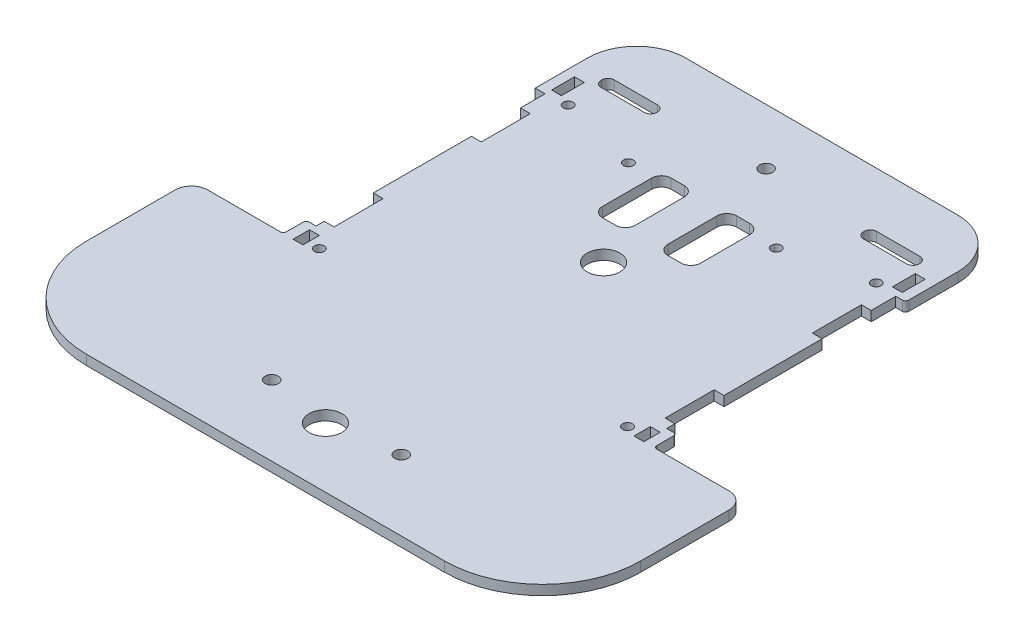
SolidWorks part; units mm, degrees
ref_plane "Front Plane" through (0, 0, 0) normal (0, 0, 1) x (1, 0, 0)
ref_plane "Top Plane" through (0, 0, 0) normal (0, 1, 0) x (1, 0, 0)
ref_plane "Right Plane" through (0, 0, 0) normal (1, 0, 0) x (0, 0, -1)
sketch "Sketch1" plane through (0, 0, 0) normal (0, 1, 0) x (1, 0, 0)
  line L7 (-95.4924, -42.3588) -> (-95.4924, -47.3588)
  line L8 (5.6997, 38.6412) -> (5.6997, 31.6412)
  line L13 (5.6997, -42.3588) -> (8.6997, -42.3588)
  line L50 (-98.4924, 31.6412) -> (-98.4924, 38.6412)
  line L51 (11.6997, 30.6412) -> (11.6997, 38.128)
  line L52 (10.6997, 29.6412) -> (8.6997, 29.6412)
  line L53 (8.6997, 22.1412) -> (8.6997, 29.6412)
  line L57 (5.6997, 22.1412) -> (8.6997, 22.1412)
  line L58 (5.6997, 22.1412) -> (5.6997, 7.1412)
  line L59 (5.6997, 7.1412) -> (8.6997, 7.1412)
  line L60 (8.6997, -22.8588) -> (8.6997, 7.1412)
  line L61 (8.6997, -22.8588) -> (5.6997, -22.8588)
  line L62 (5.6997, -22.8588) -> (5.6997, -37.8588)
  line L63 (5.6997, -37.8588) -> (8.6997, -37.8588)
  line L64 (8.6997, -40.3588) -> (8.6997, -37.8588)
  line L70 (10.6997, -40.3588) -> (8.6997, -40.3588)
  line L76 (11.6997, -46.3588) -> (11.6997, -41.3588)
  line L77 (34.787, -47.3588) -> (12.6997, -47.3588)
  line L78 (-124.5797, -47.3588) -> (-102.4924, -47.3588)
  line L79 (-101.4924, -46.3588) -> (-101.4924, -41.3588)
  line L80 (-100.4924, -40.3588) -> (-98.4924, -40.3588)
  line L86 (-98.4924, -40.3588) -> (-98.4924, -37.8588)
  line L87 (-95.4924, -37.8588) -> (-98.4924, -37.8588)
  line L88 (-95.4924, -22.8588) -> (-95.4924, -37.8588)
  line L96 (-98.4924, -22.8588) -> (-95.4924, -22.8588)
  line L97 (-98.4924, -22.8588) -> (-98.4924, 7.1412)
  line L99 (-95.4924, 7.1412) -> (-98.4924, 7.1412)
  line L103 (-95.4924, 22.1412) -> (-95.4924, 7.1412)
  line L104 (-95.4924, 22.1412) -> (-98.4924, 22.1412)
  line L105 (-98.4924, 22.1412) -> (-98.4924, 29.6412)
  line L106 (-98.4924, 29.6412) -> (-101.4924, 29.6412)
  line L107 (-101.4924, 29.6412) -> (-101.4924, 38.128)
  line L108 (-29.8964, 23.6119) -> (-29.8964, 8.6119)
  line L109 (-36.8964, 26.6119) -> (-32.8964, 26.6119)
  line L119 (-39.8964, 8.6119) -> (-39.8964, 23.6119)
  line L124 (-32.8964, 5.6119) -> (-36.8964, 5.6119)
  line L127 (-56.8964, 5.6119) -> (-52.8964, 5.6119)
  line L128 (-49.8964, 8.6119) -> (-49.8964, 23.6119)
  line L130 (-52.8964, 26.6119) -> (-56.8964, 26.6119)
  line L131 (-59.8964, 23.6119) -> (-59.8964, 8.6119)
  line L136 (-95.4924, -42.3588) -> (-98.4924, -42.3588)
  line L137 (-98.4924, -42.3588) -> (-98.4924, -47.3588)
  line L138 (-98.4924, -47.3588) -> (-95.4924, -47.3588)
  line L139 (5.6997, 31.6412) -> (8.6997, 31.6412)
  line L140 (8.6997, 38.6412) -> (8.6997, 31.6412)
  line L141 (5.6997, 38.6412) -> (8.6997, 38.6412)
  line L142 (5.6997, -42.3588) -> (5.6997, -47.3588)
  line L143 (8.6997, -47.3588) -> (5.6997, -47.3588)
  line L144 (8.6997, -42.3588) -> (8.6997, -47.3588)
  line L148 (-95.4924, 31.6412) -> (-98.4924, 31.6412)
  line L149 (-95.4924, 31.6412) -> (-95.4924, 38.6412)
  line L150 (-95.4924, 38.6412) -> (-98.4924, 38.6412)
  line L151 (-91.5924, 39.8912) -> (-78.3924, 39.8912)
  line L152 (-76.4924, 41.7912) -> (-76.4924, 41.9912)
  line L153 (-78.3924, 43.8912) -> (-91.5924, 43.8912)
  line L154 (-101.4924, 38.128) -> (-101.4924, 45.6119)
  line L156 (3.6997, 41.7912) -> (3.6997, 41.9912)
  line L157 (-93.4924, 41.7912) -> (-93.4924, 41.9912)
  line L160 (-11.4003, 43.8912) -> (1.7997, 43.8912)
  line L161 (-13.3003, 41.7912) -> (-13.3003, 41.9912)
  line L162 (1.7997, 39.8912) -> (-11.4003, 39.8912)
  line L163 (11.6997, 38.128) -> (11.6997, 45.6119)
  line L164 (-3.3003, 60.6119) -> (-86.4924, 60.6119)
  line L165 (-99.5797, -109.3881) -> (9.787, -109.3881)
  line L167 (-129.5797, -79.3881) -> (-129.5797, -52.3588)
  line L169 (39.787, -79.3881) -> (39.787, -52.3588)
  circle A72 centre (2.1997, 30.1875) radius 1.5
  circle A75 centre (2.1997, -45.8588) radius 1.5
  circle A80 centre (-91.9924, -45.8588) radius 1.5
  circle A81 centre (-91.9924, 30.1875) radius 1.5
  circle A84 centre (-24.9424, -87.8588) radius 2
  circle A85 centre (-64.5424, -87.8588) radius 2
  arc A87 (-32.8964, 5.6119) -> (-29.8964, 8.6119) centre (-32.8964, 8.6119) ccw
  arc A88 (-59.8964, 8.6119) -> (-56.8964, 5.6119) centre (-56.8964, 8.6119) ccw
  arc A90 (10.6997, 29.6412) -> (11.6997, 30.6412) centre (10.6997, 30.6412) ccw
  arc A103 (11.6997, -41.3588) -> (10.6997, -40.3588) centre (10.6997, -41.3588) ccw
  arc A104 (11.6997, -46.3588) -> (12.6997, -47.3588) centre (12.6997, -46.3588) ccw
  arc A108 (-102.4924, -47.3588) -> (-101.4924, -46.3588) centre (-102.4924, -46.3588) ccw
  arc A109 (-100.4924, -40.3588) -> (-101.4924, -41.3588) centre (-100.4924, -41.3588) ccw
  arc A112 (-29.8964, 23.6119) -> (-32.8964, 26.6119) centre (-32.8964, 23.6119) ccw
  arc A113 (-36.8964, 26.6119) -> (-39.8964, 23.6119) centre (-36.8964, 23.6119) ccw
  arc A114 (-39.8964, 8.6119) -> (-36.8964, 5.6119) centre (-36.8964, 8.6119) ccw
  arc A115 (-52.8964, 5.6119) -> (-49.8964, 8.6119) centre (-52.8964, 8.6119) ccw
  arc A116 (-49.8964, 23.6119) -> (-52.8964, 26.6119) centre (-52.8964, 23.6119) ccw
  arc A117 (-56.8964, 26.6119) -> (-59.8964, 23.6119) centre (-56.8964, 23.6119) ccw
  arc A125 (-93.4924, 41.7912) -> (-91.5924, 39.8912) centre (-91.5924, 41.7912) ccw
  arc A126 (-91.5924, 43.8912) -> (-93.4924, 41.9912) centre (-91.5924, 41.9912) ccw
  arc A127 (-76.4924, 41.7912) -> (-78.3924, 39.8912) centre (-78.3924, 41.7912) cw
  arc A128 (-76.4924, 41.9912) -> (-78.3924, 43.8912) centre (-78.3924, 41.9912) ccw
  arc A129 (-13.3003, 41.9912) -> (-11.4003, 43.8912) centre (-11.4003, 41.9912) cw
  arc A130 (-13.3003, 41.7912) -> (-11.4003, 39.8912) centre (-11.4003, 41.7912) ccw
  arc A131 (1.7997, 43.8912) -> (3.6997, 41.9912) centre (1.7997, 41.9912) cw
  arc A132 (3.6997, 41.7912) -> (1.7997, 39.8912) centre (1.7997, 41.7912) cw
  arc A133 (11.6997, 45.6119) -> (-3.3003, 60.6119) centre (-3.3003, 45.6119) ccw
  arc A134 (-101.4924, 45.6119) -> (-86.4924, 60.6119) centre (-86.4924, 45.6119) cw
  arc A139 (-129.5797, -79.3881) -> (-99.5797, -109.3881) centre (-99.5797, -79.3881) ccw
  arc A140 (9.787, -109.3881) -> (39.787, -79.3881) centre (9.787, -79.3881) ccw
  arc A141 (-129.5797, -52.3588) -> (-124.5797, -47.3588) centre (-124.5797, -52.3588) cw
  arc A142 (39.787, -52.3588) -> (34.787, -47.3588) centre (34.787, -52.3588) ccw
  circle A145 centre (-44.8964, 43.6119) radius 2
  circle A146 centre (-44.8964, -91.0715) radius 5
  circle A147 centre (-44.8964, -6.0715) radius 5
  circle A149 centre (-67.4924, 24.1119) radius 1.5
  circle A150 centre (-22.3003, 24.1119) radius 1.5
extrude "Boss-Extrude1" add sketch "Sketch1" along normal blind 3
